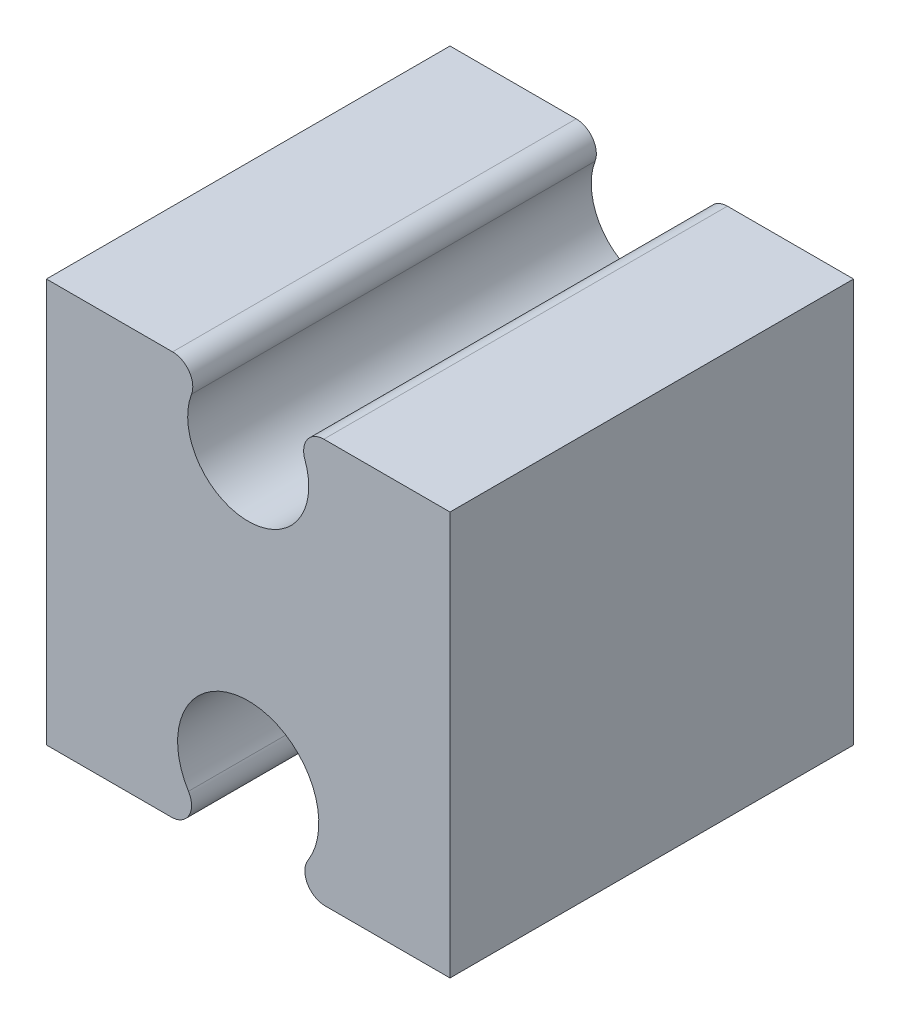
SolidWorks part; units mm, degrees
ref_plane "前视基准面" through (0, 0, 0) normal (0, 0, 1) x (1, 0, 0)
ref_plane "上视基准面" through (0, 0, 0) normal (0, 1, 0) x (1, 0, 0)
ref_plane "右视基准面" through (0, 0, 0) normal (1, 0, 0) x (0, 0, -1)
sketch "草图1" plane through (0, 0, 0) normal (0, 0, 1) x (1, 0, 0)
  line L0 (5, 0) -> (5, -0.7822) construction
  line L1 (0, 0) -> (10, 0)
  line L2 (0, 0) -> (0, -10)
  line L3 (0, -10) -> (10, -10)
  line L4 (10, 0) -> (10, -10)
  circle A0 centre (5, -1.2) radius 1.5
  circle A1 centre (5, -8.3) radius 1.75
  point P9 (0, 0)
  point P12 (0, 0)
  point P13 (0, 0)
  point P14 (0, 0)
  point P15 (0, 0)
  dimension "D1" = 3
  dimension "D5" = 1.7
  dimension "D6" = 3.5
  dimension "D2" = 1.2
  dimension "D3" = 10
  dimension "D4" = 10
extrude "凸台-拉伸1" add sketch "草图1" along normal blind 10 contours A0 L1 L2 L3 L4
fillet "圆角1" radius 0.5 4 edges at (4.1, 0, 5) (5.9, 0, 5) (5.4153, -10, 5) (4.5847, -10, 5)
equation "\"m\"= 2"
